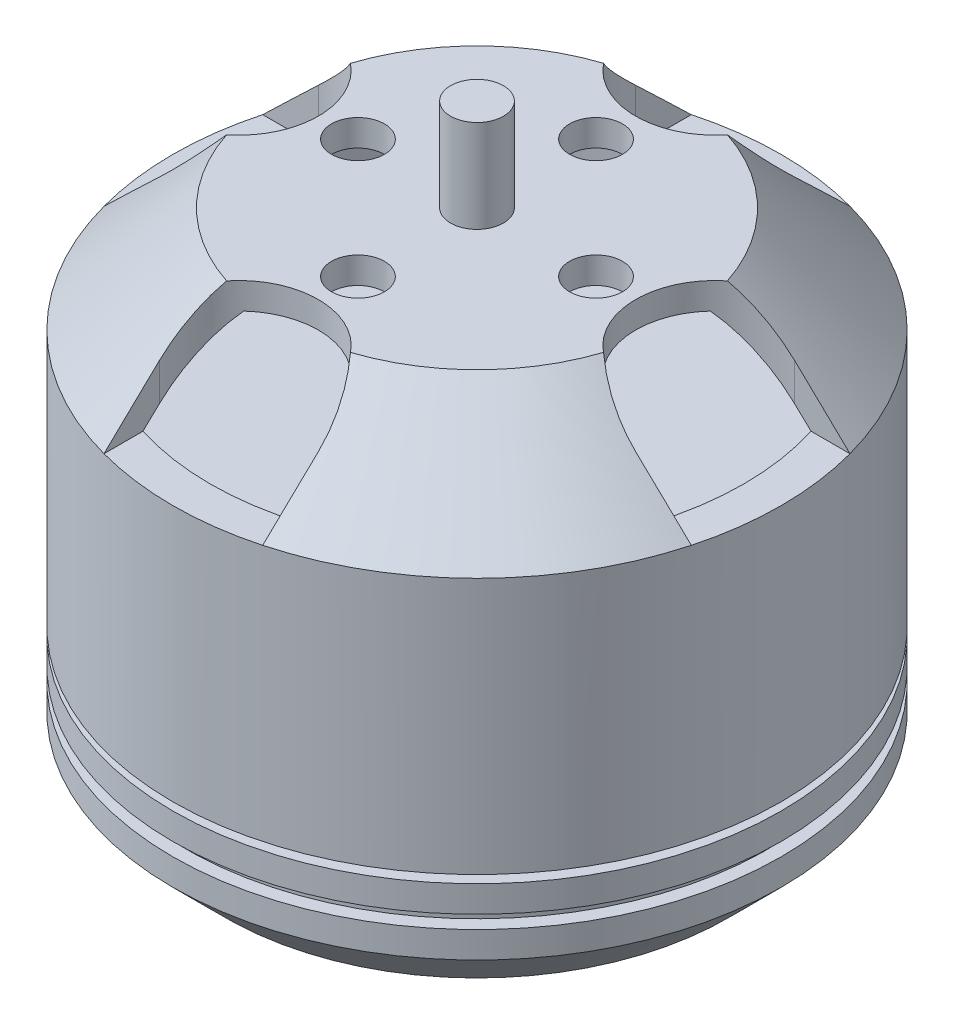
SolidWorks part; units mm, degrees
ref_plane "Front Plane" through (0, 0, 0) normal (0, 0, 1) x (1, 0, 0)
ref_plane "Top Plane" through (0, 0, 0) normal (0, 1, 0) x (1, 0, 0)
ref_plane "Right Plane" through (0, 0, 0) normal (1, 0, 0) x (0, 0, -1)
sketch "Sketch2" plane through (0, 0, 0) normal (0, 0, 1) x (1, 0, 0)
  line L0 (0, 0) -> (0, 22)
  line L1 (0, 22) -> (1, 22)
  line L2 (1, 22) -> (1, 18.5)
  line L3 (1, 18.5) -> (7.5, 18.5)
  line L4 (7.5, 18.5) -> (11.5, 14.5)
  line L5 (11.5, 14.5) -> (11.5, 4.8)
  line L6 (11.5, 4.8) -> (9.5, 4.8)
  line L7 (9.5, 4.8) -> (9.5, 4.5)
  line L8 (9.5, 4.5) -> (11.5, 4.5)
  line L9 (11.5, 4.5) -> (11.5, 3.5)
  line L10 (11.5, 3.5) -> (11, 3.5)
  line L11 (11, 3.5) -> (11, 3)
  line L12 (11, 3) -> (11.5, 3)
  line L13 (11.5, 3) -> (11.5, 2)
  line L14 (11.5, 2) -> (9.5, 0)
  line L15 (9.5, 0) -> (2, 0)
  line L16 (2, 0) -> (2, -1.8)
  line L17 (2, -1.8) -> (0, -1.8)
  line L18 (0, -1.8) -> (0, 0)
  line L19 (1, 16.5) -> (1, 10.79)
  line L20 (1, 10.79) -> (10.5, 10.79)
  line L21 (10.5, 10.79) -> (10.5, 14.0858)
  line L22 (10.5, 14.0858) -> (7.0858, 17.5)
  line L23 (7.0858, 17.5) -> (2, 17.5)
  line L24 (2, 17.5) -> (2, 16.5)
  line L25 (2, 16.5) -> (1, 16.5)
  dimension "D1" = 23.8
  dimension "D2" = 1
  dimension "D3" = 3.5
  dimension "D4" = 4
  dimension "D5" = 0.3
  dimension "D6" = 0.5
  dimension "D7" = 1
  dimension "D8" = 1
  dimension "D9" = 2
  dimension "D10" = 45
  dimension "D11" = 1.8
  dimension "D12" = 7.5
  dimension "D13" = 11.5
  dimension "D14" = 0.5
  dimension "D15" = 2
  dimension "D16" = 1
  dimension "D17" = 1
  dimension "D18" = 1
  dimension "D19" = 1
  dimension "D20" = 1
  dimension "D21" = 1
  dimension "D22" = 12.59
revolve "Revolve2" add sketch "Sketch2" angle 360 about L0
sketch "Sketch3" plane through (0, 18.5, 0) normal (0, 1, 0) x (1, 0, 0)
  line L0 (3, 9) -> (3, 18.27)
  line L1 (-3, 9) -> (-3, 18.27)
  line L2 (-3, 18.27) -> (3, 18.27)
  line L3 (9, -3) -> (18.27, -3)
  line L4 (9, 3) -> (18.27, 3)
  line L5 (18.27, 3) -> (18.27, -3)
  line L6 (-3, -9) -> (-3, -18.27)
  line L7 (3, -9) -> (3, -18.27)
  line L8 (3, -18.27) -> (-3, -18.27)
  line L9 (-9, 3) -> (-18.27, 3)
  line L10 (-9, -3) -> (-18.27, -3)
  line L11 (-18.27, -3) -> (-18.27, 3)
  circle A0 centre (0, 0) radius 4.5 construction
  circle A1 centre (0, 0) radius 9 construction
  circle A2 centre (0, 4.5) radius 1
  circle A3 centre (4.5, 0) radius 1
  circle A4 centre (0, -4.5) radius 1
  circle A5 centre (-4.5, 0) radius 1
  arc A6 (-3, 9) -> (3, 9) centre (0, 9) ccw
  arc A7 (9, 3) -> (9, -3) centre (9, 0) ccw
  arc A8 (3, -9) -> (-3, -9) centre (0, -9) ccw
  arc A9 (-9, -3) -> (-9, 3) centre (-9, 0) ccw
  point P15 (0, 0)
  point P36 (0, 0)
  dimension "D1" = 9
  dimension "D2" = 2
  dimension "D4" = 18
  dimension "D5" = 6
  dimension "D6" = 4
  dimension "D3" = 4
extrude "Cut-Extrude1" cut sketch "Sketch3" against normal blind 4
sketch "Sketch5" plane through (0, 0, 0) normal (0, -1, 0) x (1, 0, 0)
  circle A0 centre (0, 0) radius 6 construction
  circle A1 centre (0, 6) radius 1
  circle A2 centre (6, 0) radius 1
  circle A3 centre (0, -6) radius 1
  circle A4 centre (-6, 0) radius 1
  point P14 (0, 0)
  dimension "D1" = 12
  dimension "D2" = 2
  dimension "D3" = 4
extrude "Cut-Extrude2" cut sketch "Sketch5" against normal blind 3
